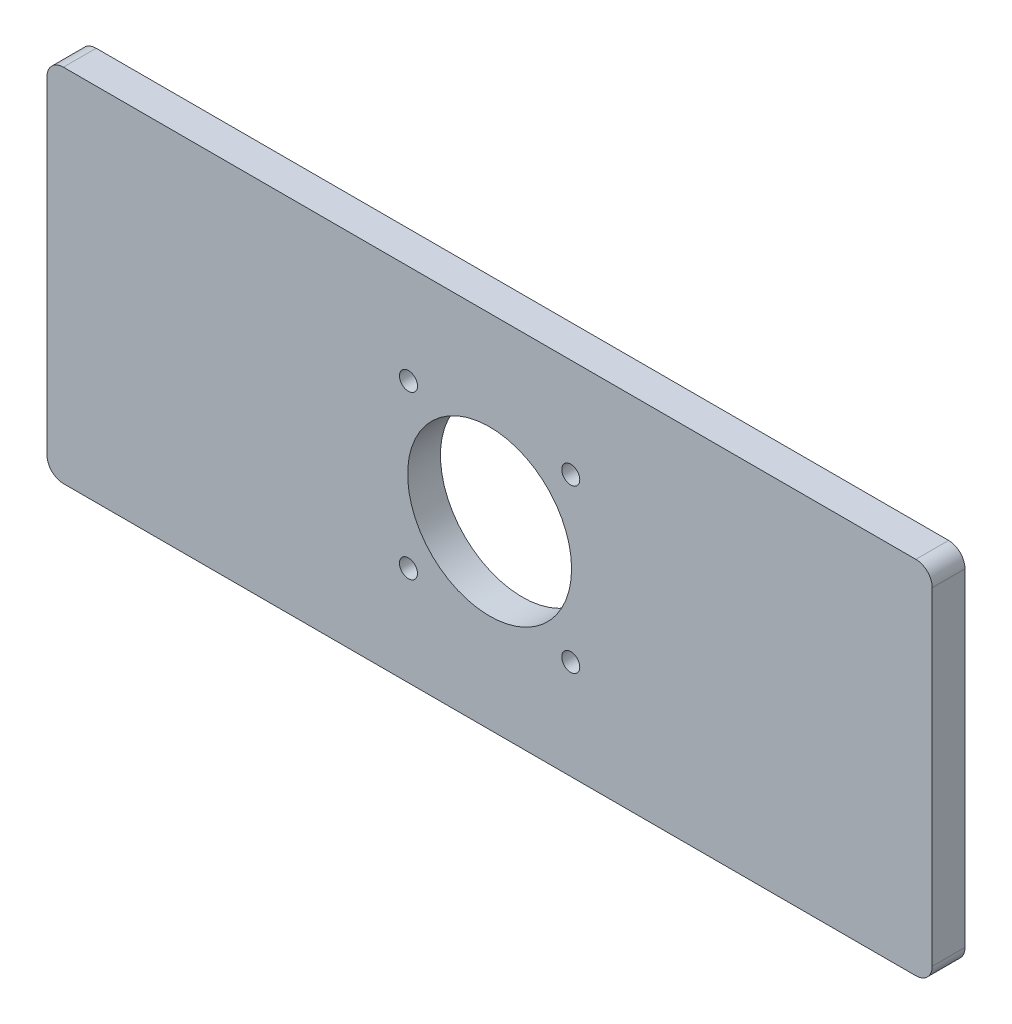
SolidWorks part; units mm, degrees
ref_plane "Front Plane" through (0, 0, 0) normal (0, 0, 1) x (1, 0, 0)
ref_plane "Top Plane" through (0, 0, 0) normal (0, 1, 0) x (1, 0, 0)
ref_plane "Right Plane" through (0, 0, 0) normal (1, 0, 0) x (0, 0, -1)
sketch "Sketch1" plane through (0, 0, 0) normal (0, 0, 1) x (1, 0, 0)
  line L0 (200, -60) -> (120, -60) construction
  line L1 (-60, 60) -> (220, 60) construction
  line L2 (-60, 60) -> (-60, -60) construction
  line L3 (-60, -60) -> (220, -60) construction
  line L4 (220, 60) -> (220, -60) construction
  line L5 (-60, -45) -> (-60, 45) construction
  line L6 (-44, 60) -> (204, 60) construction
  line L7 (220, -45) -> (220, 45) construction
  line L8 (-55, 50) -> (-55, -50)
  line L9 (-50, -55) -> (210, -55)
  line L10 (215, 50) -> (215, -50)
  line L11 (-50, 55) -> (210, 55)
  line L12 (-55, -55) -> (215, -55) construction
  line L13 (215, 55) -> (215, -55) construction
  line L14 (-55, 55) -> (215, 55) construction
  line L15 (-55, 55) -> (-55, -55) construction
  arc A0 (210, -55) -> (215, -50) centre (210, -50) ccw
  arc A1 (215, 50) -> (210, 55) centre (210, 50) ccw
  arc A2 (-55, 50) -> (-50, 55) centre (-50, 50) cw
  arc A3 (-55, -50) -> (-50, -55) centre (-50, -50) ccw
  dimension "D2" = 5
  dimension "D1" = 5
extrude "Boss-Extrude1" add sketch "Sketch1" along normal blind 10
extrude "Cut-Extrude1" cut sketch "Sketch2" against normal through all
sketch "Sketch2" plane through (-479.8458, 288.9049, 10) normal (0, 0, 1) x (1, 0, 0)
  circle A0 centre (559.8458, -288.9049) radius 25
hole_wizard "M5 Clearance Hole1" positions "Sketch3" profile "Sketch4" hole size "M5" standard "ISO" end condition through all
sketch "Sketch3" plane through (-479.8458, 288.9049, 10) normal (0, 0, 1) x (1, 0, 0)
  point P0 (535.0971, -264.1562)
  point P3 (584.5945, -264.1562)
  point P6 (584.5945, -313.6537)
  point P9 (535.0971, -313.6537)
sketch "Sketch4" plane through (55.2513, 24.7487, 10) normal (1, 0, 0) x (0, -1, 0)
  line L0 (0, 0) -> (0, 10)
  line L1 (0, 10) -> (2.75, 10)
  line L2 (2.75, 10) -> (2.75, 0)
  line L3 (2.75, 0) -> (0, 0)
  line L4 (0, -6.35) -> (0, 107.95) construction
  dimension "Thru Hole Dia." = 5.5
  dimension "Thru Hole Depth" = 10
